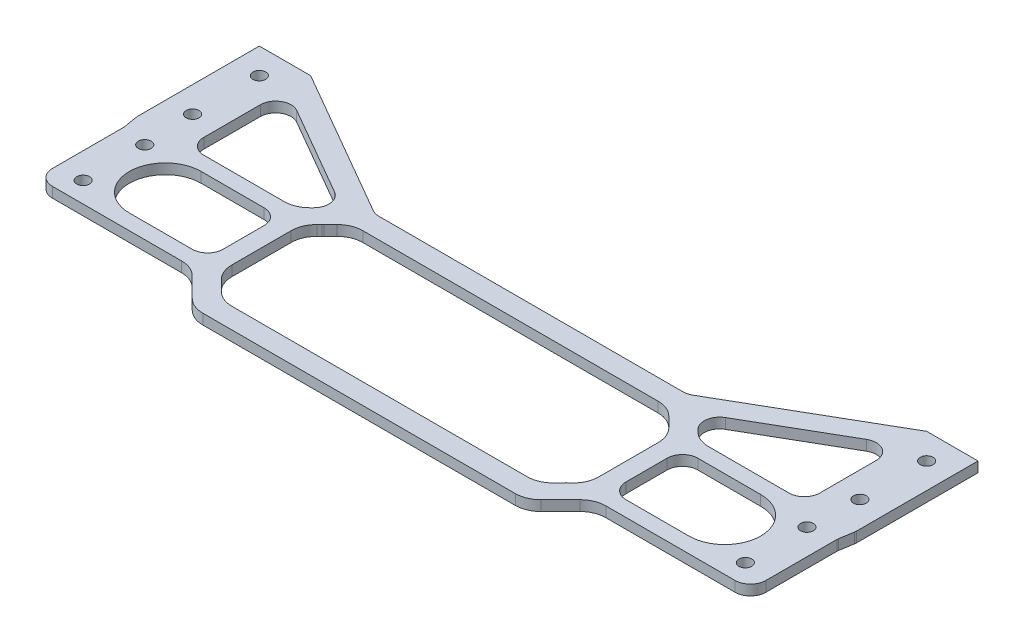
SolidWorks part; units mm, degrees
material "Thornel Mat VMA"
ref_plane "前视基准面" through (0, 0, 0) normal (0, 0, 1) x (1, 0, 0)
ref_plane "上视基准面" through (0, 0, 0) normal (0, 1, 0) x (1, 0, 0)
ref_plane "右视基准面" through (0, 0, 0) normal (1, 0, 0) x (0, 0, -1)
sketch "草图1" plane through (0, 0, 0) normal (0, 1, 0) x (1, 0, 0)
  line L1 (66.5, 10) -> (-66.5, 10)
  line L2 (69.5, 7) -> (69.5, -7)
  line L3 (66.5, -10) -> (-66.5, -10)
  line L4 (-69.5, 7) -> (-69.5, -7)
  line L5 (69.5, 10) -> (-69.5, -10) construction
  line L6 (69.5, -10) -> (-69.5, 10) construction
  arc A0 (69.5, 7) -> (66.5, 10) centre (66.5, 7) ccw
  arc A1 (69.5, -7) -> (66.5, -10) centre (66.5, -7) cw
  arc A2 (-66.5, -10) -> (-69.5, -7) centre (-66.5, -7) cw
  arc A3 (-66.5, 10) -> (-69.5, 7) centre (-66.5, 7) ccw
  point P0 (0, 0)
  dimension "D3" = 3
  dimension "D1" = 20
  dimension "D2" = 139
extrude "凸台-拉伸1" add sketch "草图1" along normal blind 2
sketch "草图2" plane through (0, 2, 0) normal (0, 1, 0) x (1, 0, 0)
  line L1 (64.5, 6) -> (-64.5, 6)
  line L2 (64.5, 6) -> (64.5, -6)
  line L3 (64.5, -6) -> (-64.5, -6)
  line L4 (-64.5, 6) -> (-64.5, -6)
  line L5 (64.5, 6) -> (-64.5, -6) construction
  line L6 (64.5, -6) -> (-64.5, 6) construction
  point P0 (0, 0)
  dimension "D1" = 12
  dimension "D2" = 129
hole_wizard "孔1" positions "草图3" profile "草图4" legacy end condition through all
sketch "草图3" plane through (0, 2, 0) normal (0, 1, 0) x (1, 0, 0)
  point P0 (-64.5, 6)
  point P3 (-64.5, -6)
  point P6 (64.5, -6)
  point P9 (64.5, 6)
sketch "草图4" plane through (-64.5, 2, -6) normal (1, 0, 0) x (0, 0, 1)
  line L0 (0, 0) -> (0, 2)
  line L1 (0, 2) -> (1.25, 2)
  line L2 (1.25, 2) -> (1.25, 0)
  line L3 (1.25, 0) -> (0, 0)
  line L4 (0, 110) -> (0, -10) construction
  dimension "直径" = 2.5
  dimension "深度" = 2
sketch "草图5" plane through (0, 2, 0) normal (0, 1, 0) x (1, 0, 0)
  line L0 (-54.5, 0) -> (54.5, 0) construction
  line L1 (-54.5, 7) -> (54.5, 7)
  line L2 (-54.5, -7) -> (54.5, -7)
  line L3 (66.5, 10) -> (-66.5, 10) construction
  line L4 (-69.5, 7) -> (-69.5, -7) construction
  arc A0 (-54.5, 7) -> (-54.5, -7) centre (-54.5, 0) ccw
  arc A1 (54.5, -7) -> (54.5, 7) centre (54.5, 0) ccw
  point P3 (0, 0)
  dimension "D1" = 3
  dimension "D2" = 15
extrude "切除-拉伸1" cut sketch "草图5" against normal through all
sketch "草图6" plane through (0, 0, 0) normal (0, -1, 0) x (1, 0, 0)
  line L0 (-66.5, 10) -> (66.5, 10) construction
  line L1 (-39.25, -10) -> (39.25, -10)
  line L2 (-39.25, -4) -> (-39.25, 4)
  line L3 (-39.25, 10) -> (39.25, 10)
  line L4 (39.25, -4) -> (39.25, 4)
  line L5 (-39.25, -10) -> (39.25, 10) construction
  line L6 (-39.25, 10) -> (39.25, -10) construction
  line L7 (39.25, -23.75) -> (39.25, 23.75) construction
  line L8 (39.25, 10) -> (46.786, 7)
  line L9 (-54.5, 7) -> (54.5, 7) construction
  line L10 (46.786, 7) -> (42.25, 7)
  line L11 (39.25, -10) -> (46.786, -7)
  line L12 (54.5, -7) -> (-54.5, -7) construction
  line L13 (46.786, -7) -> (42.25, -7)
  line L14 (-39.25, 10) -> (-46.7861, 7)
  line L15 (-46.7861, 7) -> (-42.25, 7)
  line L16 (-39.25, -10) -> (-46.4944, -7)
  line L17 (-46.4944, -7) -> (-42.25, -7)
  line L18 (-39.25, 23.75) -> (-39.25, -23.75) construction
  arc A0 (39.25, -4) -> (42.25, -7) centre (42.25, -4) ccw
  arc A1 (39.25, 4) -> (42.25, 7) centre (42.25, 4) cw
  arc A2 (-42.25, -7) -> (-39.25, -4) centre (-42.25, -4) ccw
  arc A3 (-39.25, 4) -> (-42.25, 7) centre (-42.25, 4) ccw
  point P0 (0, 0)
  point P26 (39.25, -7)
  point P29 (39.25, 7)
  point P32 (-39.25, -7)
  point P35 (-39.25, 7)
  dimension "D1" = 3
extrude "凸台-拉伸2" add sketch "草图6" against normal blind 2
sketch "草图7" plane through (0, 0, 0) normal (0, -1, 0) x (1, 0, 0)
  line L0 (34.25, 0) -> (-34.25, 0) construction
  line L1 (34.25, -1.5) -> (-34.25, -1.5)
  line L2 (34.25, 1.5) -> (-34.25, 1.5)
  line L3 (39.25, -4) -> (39.25, 4) construction
  line L4 (34.25, 5.5) -> (-34.25, 5.5) construction
  line L5 (34.25, 4) -> (-34.25, 4)
  line L6 (34.25, 7) -> (-34.25, 7)
  line L7 (34.25, -5.5) -> (-34.25, -5.5) construction
  line L8 (34.25, -7) -> (-34.25, -7)
  line L9 (34.25, -4) -> (-34.25, -4)
  arc A0 (34.25, -1.5) -> (34.25, 1.5) centre (34.25, 0) ccw
  arc A1 (-34.25, 1.5) -> (-34.25, -1.5) centre (-34.25, 0) ccw
  arc A2 (34.25, 4) -> (34.25, 7) centre (34.25, 5.5) ccw
  arc A3 (-34.25, 7) -> (-34.25, 4) centre (-34.25, 5.5) ccw
  arc A4 (34.25, -7) -> (34.25, -4) centre (34.25, -5.5) ccw
  arc A5 (-34.25, -4) -> (-34.25, -7) centre (-34.25, -5.5) ccw
  point P3 (0, 0)
  point P14 (0, 5.5)
  point P21 (0, -5.5)
  dimension "D1" = 1.5
  dimension "D2" = 5
  dimension "D4" = 5.5
  dimension "D3" = 2
  dimension "D5" = 2
extrude "切除-拉伸2" cut sketch "草图7" against normal through all both and the other way through all
sketch "草图9" plane through (0, 0, 0) normal (0, -1, 0) x (-1, 0, 0)
  line L0 (47.6578, -10) -> (41.3211, -10)
  line L1 (66.5, -10) -> (-66.5, -10) construction
  line L2 (39.25, -23.75) -> (39.25, 23.75) construction
  line L3 (37.7855, -11.4645) -> (33.9645, -15.2855)
  line L4 (30.4289, -16.75) -> (-30.4289, -16.75)
  line L5 (0, 87.7971) -> (0, -87.7971) construction
  line L6 (39.25, -10) -> (33.5931, -10)
  line L7 (33.5931, -10) -> (32.3076, -11.2855)
  line L8 (28.7721, -12.75) -> (-28.7721, -12.75)
  line L9 (-36.25, -26.75) -> (36.25, -26.75) construction
  line L10 (47.6578, -10) -> (47.6578, -7.8784)
  line L11 (47.6578, -7.8784) -> (24.5865, -7.8784)
  line L12 (24.5865, -7.8784) -> (24.5865, -10)
  line L13 (24.5865, -10) -> (33.5931, -10)
  line L14 (0, -16.75) -> (0, 0) construction
  line L15 (-31.7712, 0) -> (31.7712, 0) construction
  line L16 (24.5865, 10) -> (33.5931, 10)
  line L17 (24.5865, 7.8784) -> (24.5865, 10)
  line L18 (47.6578, 7.8784) -> (24.5865, 7.8784)
  line L19 (47.6578, 10) -> (47.6578, 7.8784)
  line L20 (28.7721, 12.75) -> (-28.7721, 12.75)
  line L21 (33.5931, 10) -> (32.3076, 11.2855)
  line L22 (39.25, 10) -> (33.5931, 10)
  line L23 (30.4289, 16.75) -> (-30.4289, 16.75)
  line L24 (37.7855, 11.4645) -> (33.9645, 15.2855)
  line L25 (47.6578, 10) -> (41.3211, 10)
  line L26 (-47.6578, 10) -> (-41.3211, 10)
  line L27 (-37.7855, 11.4645) -> (-33.9645, 15.2855)
  line L28 (-39.25, 10) -> (-33.5931, 10)
  line L29 (-33.5931, 10) -> (-32.3076, 11.2855)
  line L30 (-47.6578, 10) -> (-47.6578, 7.8784)
  line L31 (-47.6578, 7.8784) -> (-24.5865, 7.8784)
  line L32 (-24.5865, 7.8784) -> (-24.5865, 10)
  line L33 (-24.5865, 10) -> (-33.5931, 10)
  line L34 (-24.5865, -10) -> (-33.5931, -10)
  line L35 (-24.5865, -7.8784) -> (-24.5865, -10)
  line L36 (-47.6578, -7.8784) -> (-24.5865, -7.8784)
  line L37 (-47.6578, -10) -> (-47.6578, -7.8784)
  line L38 (-33.5931, -10) -> (-32.3076, -11.2855)
  line L39 (-39.25, -10) -> (-33.5931, -10)
  line L40 (-37.7855, -11.4645) -> (-33.9645, -15.2855)
  line L41 (-47.6578, -10) -> (-41.3211, -10)
  arc A0 (28.7721, -12.75) -> (32.3076, -11.2855) centre (28.7721, -7.75) ccw
  arc A1 (37.7855, -11.4645) -> (41.3211, -10) centre (41.3211, -15) cw
  arc A2 (30.4289, -16.75) -> (33.9645, -15.2855) centre (30.4289, -11.75) ccw
  arc A3 (30.4289, 16.75) -> (33.9645, 15.2855) centre (30.4289, 11.75) cw
  arc A4 (37.7855, 11.4645) -> (41.3211, 10) centre (41.3211, 15) ccw
  arc A5 (28.7721, 12.75) -> (32.3076, 11.2855) centre (28.7721, 7.75) cw
  arc A6 (-28.7721, 12.75) -> (-32.3076, 11.2855) centre (-28.7721, 7.75) ccw
  arc A7 (-37.7855, 11.4645) -> (-41.3211, 10) centre (-41.3211, 15) cw
  arc A8 (-30.4289, 16.75) -> (-33.9645, 15.2855) centre (-30.4289, 11.75) ccw
  arc A9 (-30.4289, -16.75) -> (-33.9645, -15.2855) centre (-30.4289, -11.75) cw
  arc A10 (-37.7855, -11.4645) -> (-41.3211, -10) centre (-41.3211, -15) ccw
  arc A11 (-28.7721, -12.75) -> (-32.3076, -11.2855) centre (-28.7721, -7.75) cw
  point P65 (0, 16.75)
  point P67 (0, 12.75)
  point P75 (0, -12.75)
  line M31 (66.5, 10) -> (-66.5, 10)
  line M35 (-66.5, -10) -> (66.5, -10)
  dimension "D5" = 5
  dimension "D6" = 5
  dimension "D1" = 4
  dimension "D2" = 45
  dimension "D3" = 4
  dimension "D4" = 10
extrude "凸台-拉伸3" add sketch "草图9" against normal blind 2 contours L8 A11 L38 A10 L40 A9 L4 A2 L3 A1 L7 A0 M35 | L23 A8 L27 A7 L29 A6 L20 A5 L21 A4 L24 A3 M31
sketch "草图10" plane through (0, 2, 0) normal (0, 1, 0) x (1, 0, 0)
  line L0 (34.2855, -9.3076) -> (34.098, -9.4951)
  line L2 (-35.75, -5.7721) -> (-35.75, 5.7721)
  line L4 (35.75, -5.7721) -> (35.75, 5.7721)
  line L5 (-35.75, -7.8431) -> (35.75, 7.8431) construction
  line L6 (-35.75, 7.8431) -> (35.75, -7.8431) construction
  line L7 (33.5931, -10) -> (32.3076, -11.2855) construction
  line L8 (30.5884, -10.9595) -> (-30.2214, -11.2747)
  line L9 (-33.7828, -9.8103) -> (-34.2855, -9.3076)
  line L10 (34.2855, 9.3076) -> (33.7721, 9.8211)
  line L11 (30.2365, 11.2855) -> (-30.2365, 11.2855)
  line L12 (-33.7721, 9.8211) -> (-34.2855, 9.3076)
  arc A0 (34.25, 4) -> (34.25, 7) centre (34.25, 5.5) ccw construction
  arc A1 (-35.75, -5.7721) -> (-34.2855, -9.3076) centre (-30.75, -5.7721) ccw
  arc A2 (-33.7828, -9.8103) -> (-30.2214, -11.2747) centre (-30.2473, -6.2748) ccw
  arc A3 (-35.75, 5.7721) -> (-34.2855, 9.3076) centre (-30.75, 5.7721) cw
  arc A4 (-33.7721, 9.8211) -> (-30.2365, 11.2855) centre (-30.2365, 6.2855) cw
  arc A5 (30.2365, 11.2855) -> (33.7721, 9.8211) centre (30.2365, 6.2855) cw
  arc A6 (34.2855, 9.3076) -> (35.75, 5.7721) centre (30.75, 5.7721) cw
  arc A7 (35.75, -5.7721) -> (34.2855, -9.3076) centre (30.75, -5.7721) cw
  arc A8 (30.5884, -10.9595) -> (34.098, -9.4951) centre (30.5625, -5.9596) ccw
  point P0 (0, 0)
  point P23 (-32.3076, -11.2855)
  point P29 (-32.3076, 11.2855)
  point P32 (32.3076, 11.2855)
  point P41 (32.6443, -10.9489)
  dimension "D1" = 5
extrude "切除-拉伸3" cut sketch "草图10" against normal through all both and the other way through all
sketch "草图11" plane through (0, 0, 0) normal (0, -1, 0) x (1, 0, 0)
  line L0 (-70, -10.1655) -> (-70, -33.8229)
  line L1 (-70, -10) -> (-70, -220) construction
  line L2 (-70, -33.8229) -> (-60, -33.8229)
  line L3 (-60, -10) -> (-60, -220) construction
  line L4 (-30.4289, -16.75) -> (30.4289, -16.75) construction
  line L5 (-60, -33.8229) -> (-31.1251, -17.1519)
  line L6 (0, -12.75) -> (0, -43.4352) construction
  line L7 (-38.056, -16.5347) -> (-55.5, -26.606)
  line L8 (-60, -24.0079) -> (-60, -13)
  line L9 (-41.3211, -10) -> (-66.5, -10) construction
  line L10 (-57, -10) -> (-53.1843, -10)
  line L11 (-53.1843, -10) -> (-53.1843, -8.5095)
  line L12 (-53.1843, -8.5095) -> (-68.3017, -8.5095)
  line L13 (68.3017, -8.5095) -> (69.5, -3.5347)
  line L14 (-39.9409, -9.3091) -> (-37.4347, -11.8153)
  line L15 (-37.7855, -11.4645) -> (-33.9645, -15.2855) construction
  line L16 (-39.9409, -9.3091) -> (-32.2298, -13.6308)
  line L17 (-32.2298, -13.6308) -> (-21.7891, -16.75)
  line L18 (-21.7891, -16.75) -> (-29.6251, -16.75)
  line L19 (-28.7721, -12.75) -> (28.7721, -12.75) construction
  line L20 (0, -87.7971) -> (0, 87.7971) construction
  line L21 (21.7891, -16.75) -> (29.6251, -16.75)
  line L22 (32.2298, -13.6308) -> (21.7891, -16.75)
  line L23 (39.9409, -9.3091) -> (32.2298, -13.6308)
  line L24 (39.9409, -9.3091) -> (37.4347, -11.8153)
  line L25 (69.5, 7) -> (69.5, -7) construction
  line L26 (53.1843, -8.5095) -> (68.3017, -8.5095)
  line L27 (53.1843, -10) -> (53.1843, -8.5095)
  line L28 (57, -10) -> (53.1843, -10)
  line L29 (60, -24.0079) -> (60, -13)
  line L30 (38.056, -16.5347) -> (55.5, -26.606)
  line L31 (60, -33.8229) -> (31.1251, -17.1519)
  line L32 (70, -33.8229) -> (60, -33.8229)
  line L33 (70, -10.1655) -> (70, -33.8229)
  line L34 (-69.9728, -9.8367) -> (-69.5272, -7.1633)
  line L35 (-69.5, -6.8345) -> (-69.5, -3.1846)
  line L36 (-69.5, -7) -> (-69.5, 7) construction
  line L37 (-69.5, -3.1846) -> (-68.3017, -8.5095)
  line L38 (69.5, -3.5347) -> (69.5, -6.8345)
  line L39 (69.5272, -7.1633) -> (69.9728, -9.8367)
  arc A0 (-38.056, -16.5347) -> (-37.4347, -11.8153) centre (-39.556, -13.9366) ccw
  arc A1 (-55.5, -26.606) -> (-60, -24.0079) centre (-57, -24.0079) cw
  arc A2 (-60, -13) -> (-57, -10) centre (-57, -13) cw
  arc A3 (-29.6251, -16.75) -> (-31.1251, -17.1519) centre (-29.6251, -19.75) ccw
  arc A4 (29.6251, -16.75) -> (31.1251, -17.1519) centre (29.6251, -19.75) cw
  arc A5 (60, -13) -> (57, -10) centre (57, -13) ccw
  arc A6 (55.5, -26.606) -> (60, -24.0079) centre (57, -24.0079) ccw
  arc A7 (38.056, -16.5347) -> (37.4347, -11.8153) centre (39.556, -13.9366) cw
  arc A8 (70, -10.1655) -> (69.9728, -9.8367) centre (68, -10.1655) ccw
  arc A9 (-70, -10.1655) -> (-69.9728, -9.8367) centre (-68, -10.1655) cw
  arc A10 (-69.5272, -7.1633) -> (-69.5, -6.8345) centre (-71.5, -6.8345) ccw
  arc A11 (69.5272, -7.1633) -> (69.5, -6.8345) centre (71.5, -6.8345) cw
  point P25 (-30.4289, -16.75)
  point P28 (-34.6701, -14.5799)
  point P31 (-60, -29.2041)
  point P34 (-60, -10)
  point P64 (60, -10)
  point P65 (60, -29.2041)
  point P66 (34.6701, -14.5799)
  point P67 (30.4289, -16.75)
  point P84 (-70, -10)
  point P87 (-69.5, -7)
  point P90 (69.5, -7)
  dimension "D1" = 3
  dimension "D3" = 3
  dimension "D5" = 2
  dimension "D2" = 150
  dimension "D4" = 4
extrude "凸台-拉伸4" add sketch "草图11" against normal blind 2
hole_wizard "孔2" positions "草图12" profile "草图13" legacy end condition through all
sketch "草图12" plane through (0, 0, 0) normal (0, -1, 0) x (-1, 0, 0)
  point P0 (65, 15.8229)
  point P3 (65, 28.8229)
  point P6 (-65, 15.8229)
  point P9 (-65, 28.8229)
sketch "草图13" plane through (-65, 0, -15.8229) normal (1, 0, 0) x (0, 0, -1)
  line L0 (0, 0) -> (0, 2)
  line L1 (0, 2) -> (1.25, 2)
  line L2 (1.25, 2) -> (1.25, 0)
  line L3 (1.25, 0) -> (0, 0)
  line L4 (0, 110) -> (0, -10) construction
  dimension "直径" = 2.5
  dimension "深度" = 2
